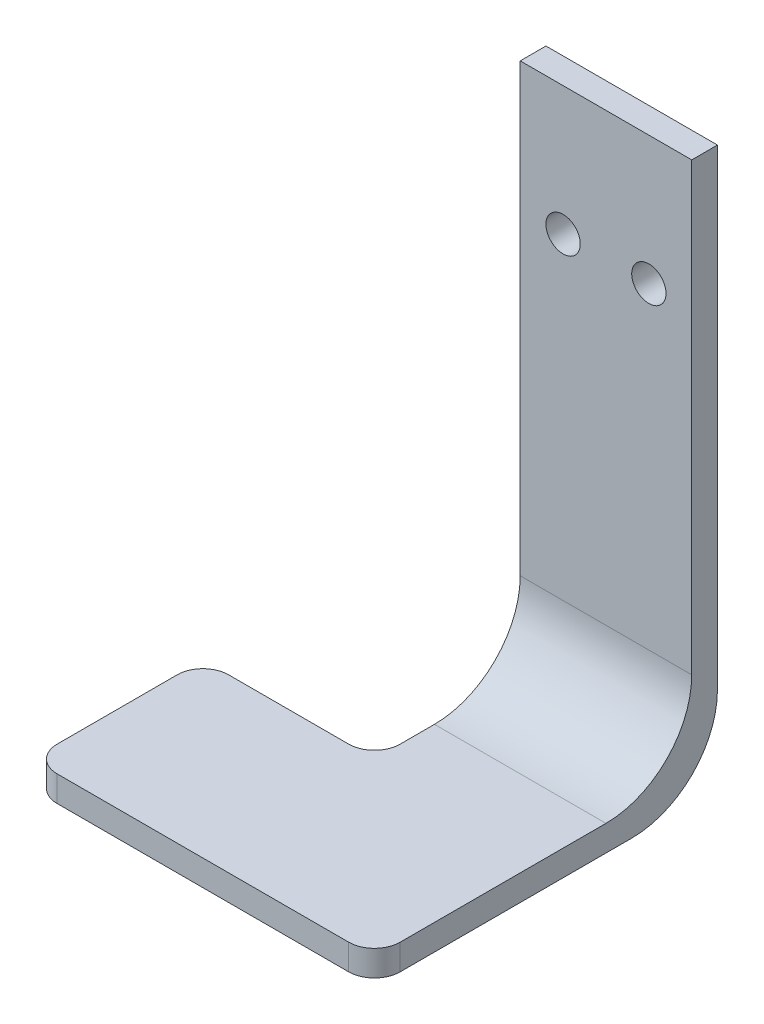
SolidWorks part; units mm, degrees
ref_plane "前视基准面" through (0, 0, 0) normal (0, 0, 1) x (1, 0, 0)
ref_plane "上视基准面" through (0, 0, 0) normal (0, 1, 0) x (1, 0, 0)
ref_plane "右视基准面" through (0, 0, 0) normal (1, 0, 0) x (0, 0, -1)
sketch "草图1" plane through (0, 0, 0) normal (0, 0, 1) x (1, 0, 0)
  line L0 (0, 0) -> (0, -65) construction
  line L1 (-10, 0) -> (10, 0)
  line L2 (-10, 0) -> (-10, -65)
  line L3 (-10, -65) -> (10, -65)
  line L4 (10, 0) -> (10, -65)
  circle A0 centre (-5, -15) radius 2
  circle A1 centre (5, -15) radius 2
  point P4 (0, 0)
  point P12 (0, 0)
  point P13 (-4.3234, -15)
  dimension "D3" = 4
  dimension "D1" = 65
  dimension "D2" = 20
  dimension "D4" = 10
  dimension "D5" = 15
extrude "凸台-拉伸1" add sketch "草图1" along normal blind 3
sketch "草图2" plane through (0, 0, 0) normal (0, 0, 1) x (1, 0, 0)
  line L0 (10, -65) -> (10, 0) construction
  line L1 (-30, -65) -> (10, -65)
  line L2 (-30, -65) -> (-30, -62)
  line L3 (-30, -62) -> (10, -62)
  line L4 (10, -65) -> (10, -62)
  line L5 (-10, -65) -> (10, -65) construction
  dimension "D1" = 3
  dimension "D2" = 40
extrude "凸台-拉伸2" add sketch "草图2" along normal blind 40
sketch "草图3" plane through (0, -62, 0) normal (0, 1, 0) x (1, 0, 0)
  line L0 (-10, -3) -> (-10, 0) construction
  line L1 (-30, 0) -> (-10, 0)
  line L2 (-30, 0) -> (-30, -20)
  line L3 (-30, -20) -> (-10, -20)
  line L4 (-10, 0) -> (-10, -20)
  point P5 (-13.1007, 0)
  dimension "D1" = 20
extrude "切除-拉伸1" cut sketch "草图3" against normal blind 3
fillet "圆角1" radius 10 2 edges at (0, -65, 0) (0, -62, 3)
fillet "圆角2" radius 3 4 edges at (10, -63.5, 40) (-10, -63.5, 20) (-30, -63.5, 20) (-30, -63.5, 40)
